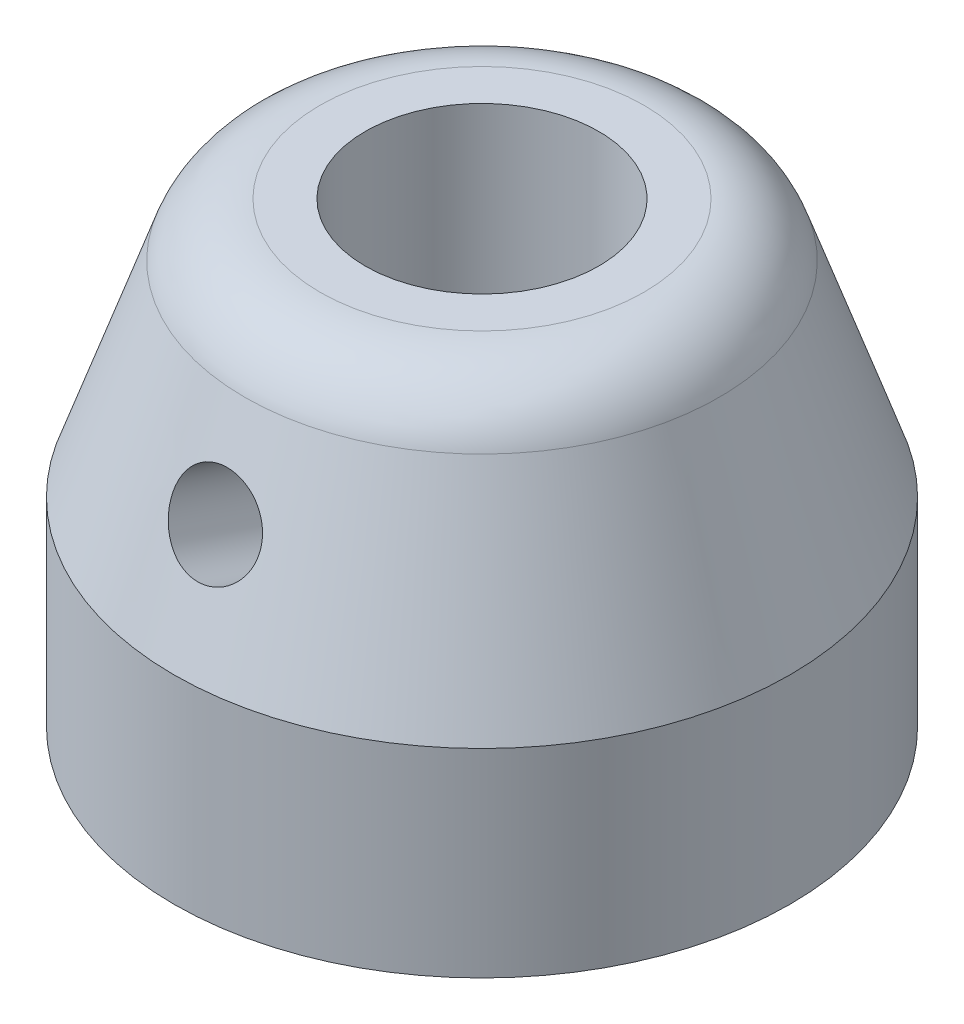
SolidWorks part; units mm, degrees
material "Plain Carbon Steel"
ref_plane "Front Plane" through (0, 0, 0) normal (0, 0, 1) x (1, 0, 0)
ref_plane "Top Plane" through (0, 0, 0) normal (0, 1, 0) x (1, 0, 0)
ref_plane "Right Plane" through (0, 0, 0) normal (1, 0, 0) x (0, 0, -1)
sketch "Sketch1" plane through (0, 0, 0) normal (0, 0, 1) x (1, 0, 0)
  line L0 (0, 17.6828) -> (0, -30.457) construction
  line L1 (0, 12.4785) -> (22, 12.4785)
  line L2 (22, 12.4785) -> (31, -13.5215)
  line L3 (31, -13.5215) -> (31, -33.5215)
  line L4 (31, -33.5215) -> (0, -33.5215)
  line L5 (0, -33.5215) -> (0, 12.4785)
  dimension "D1" = 22
  dimension "D2" = 46
  dimension "D3" = 31
  dimension "D4" = 20
revolve "Revolve1" add sketch "Sketch1" angle 360 about L0
hole_wizard "M25x1.5 Tapped Hole2" positions "Sketch4" profile "Sketch5" tap size "M25x1.5" standard "DIN" end condition through all
sketch "Sketch4" plane through (0, 12.4785, 0) normal (0, 1, 0) x (1, 0, 0)
  point P0 (0, 0)
sketch "Sketch5" plane through (0, 12.4785, 0) normal (1, 0, 0) x (0, 0, 1)
  line L0 (0, 0) -> (0, 46)
  line L1 (0, 46) -> (11.75, 46)
  line L2 (11.75, 46) -> (11.75, 0)
  line L5 (11.75, 0) -> (0, 0)
  line L11 (0, -6.35) -> (0, 107.95) construction
  dimension "Thru Tap Drill Dia." = 23.5
  dimension "Thru Tap Drill Depth" = 46
cosmetic thread "Hole Thread2"
fillet "Fillet1" radius 8 1 edges at (0, 12.4785, 22)
sketch "Sketch6" plane through (0, 0, 0) normal (1, 0, 0) x (0, 0, -1)
  line L0 (-23.8634, 7.0954) -> (-31, -13.5215) construction
  line L1 (-23.8634, 7.0954) -> (-31, -13.5215) construction
ref_plane "Plane1" through (0, 8.1357, 23.5033) normal (0, 0.3271, 0.945) x (1, 0, 0)
hole_wizard "M10x1.0 Tapped Hole1" positions "Sketch7" profile "Sketch8" tap size "M10x1.0" standard "DIN"
sketch "Sketch7" plane through (0, 8.1357, 23.5033) normal (0, 0.3271, 0.945) x (1, 0, 0)
  line L0 (0, -1.1009) -> (0, -22.9181) construction
  line L1 (0, -1.1009) -> (-7.991, -1.1009) construction
  point P0 (0, -11.1009)
  dimension "D1" = 10
sketch "Sketch8" plane through (0, -2.3545, 27.1345) normal (1, 0, 0) x (0, -0.945, 0.3271)
  line L0 (0, 0) -> (0, 12.7039)
  line L1 (0, 12.7039) -> (4.5, 10)
  line L2 (4.5, 10) -> (4.5, 0)
  line L5 (4.5, 0) -> (0, 0)
  line L10 (0, 12.7039) -> (-4.5, 10) construction
  line L11 (0, -6.35) -> (0, 107.95) construction
  dimension "Tap Drill Dia." = 9
  dimension "Tap Drill Depth" = 10
  dimension "Drill Angle" = 118
cosmetic thread "Hole Thread3"
